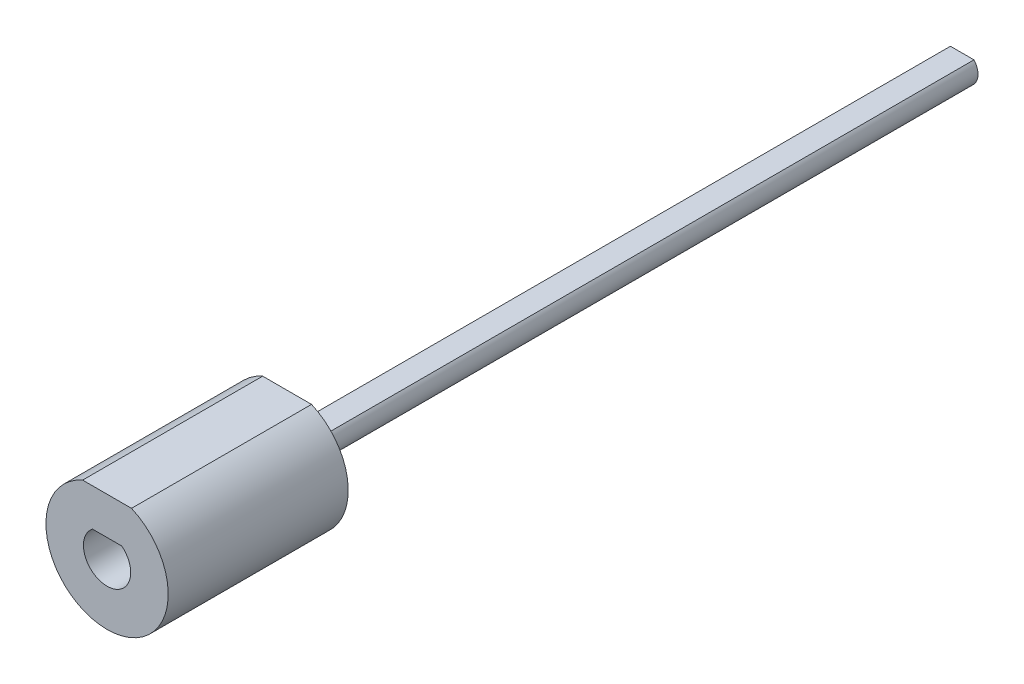
SolidWorks part; units mm, degrees
ref_plane "Front Plane" through (0, 0, 0) normal (0, 0, 1) x (1, 0, 0)
ref_plane "Top Plane" through (0, 0, 0) normal (0, 1, 0) x (1, 0, 0)
ref_plane "Right Plane" through (0, 0, 0) normal (1, 0, 0) x (0, 0, -1)
sketch "Sketch1" plane through (0, 0, 0) normal (0, 0, 1) x (1, 0, 0)
  line L0 (0, -2) -> (0, 1.5682) construction
  line L1 (-1.2413, 1.5682) -> (1.2413, 1.5682)
  line L2 (-2.0695, 4.7432) -> (2.0695, 4.7432)
  arc A0 (-1.2413, 1.5682) -> (1.2413, 1.5682) centre (0, 0) ccw
  arc A1 (-2.0695, 4.7432) -> (2.0695, 4.7432) centre (0, 0) ccw
  dimension "D1" = 4
  dimension "D2" = 3.5682
  dimension "D3" = 3.175
extrude "Boss-Extrude1" add sketch "Sketch1" along normal blind 6.35
sketch "Sketch3" plane through (0, 0, 0) normal (0, 0, -1) x (-1, 0, 0)
  line L0 (-2.0695, 4.7432) -> (2.0695, 4.7432) construction
  line L1 (-2.0695, 4.7432) -> (2.0695, 4.7432)
  arc A0 (-2.0695, 4.7432) -> (2.0695, 4.7432) centre (0, 0) ccw construction
  arc A1 (-2.0695, 4.7432) -> (2.0695, 4.7432) centre (0, 0) ccw
extrude "Boss-Extrude2" add sketch "Sketch3" along normal blind 2.54
sketch "Sketch4" plane through (0, 0, -2.54) normal (0, 0, -1) x (-1, 0, 0)
  line L0 (2.0695, 4.7432) -> (-2.0695, 4.7432) construction
  line L1 (2.0695, 4.7432) -> (-2.0695, 4.7432)
  arc A0 (-2.0695, 4.7432) -> (2.0695, 4.7432) centre (0, 0) ccw construction
  arc A1 (-2.0695, 4.7432) -> (2.0695, 4.7432) centre (0, 0) ccw
  circle A2 centre (0, 0) radius 1.5113
  dimension "D1" = 3.0226
extrude "Boss-Extrude4" add sketch "Sketch4" along normal blind 6.35
sketch "Sketch2" plane through (0, 0, -2.54) normal (0, 0, -1) x (-1, 0, 0)
  line L1 (0.9977, 0.8924) -> (-0.9977, 0.8924)
  arc A1 (-0.9977, 0.8924) -> (0.9977, 0.8924) centre (0, 0) ccw
  dimension "D1" = 1.3386
extrude "Boss-Extrude3" add sketch "Sketch2" along normal blind 63.5
